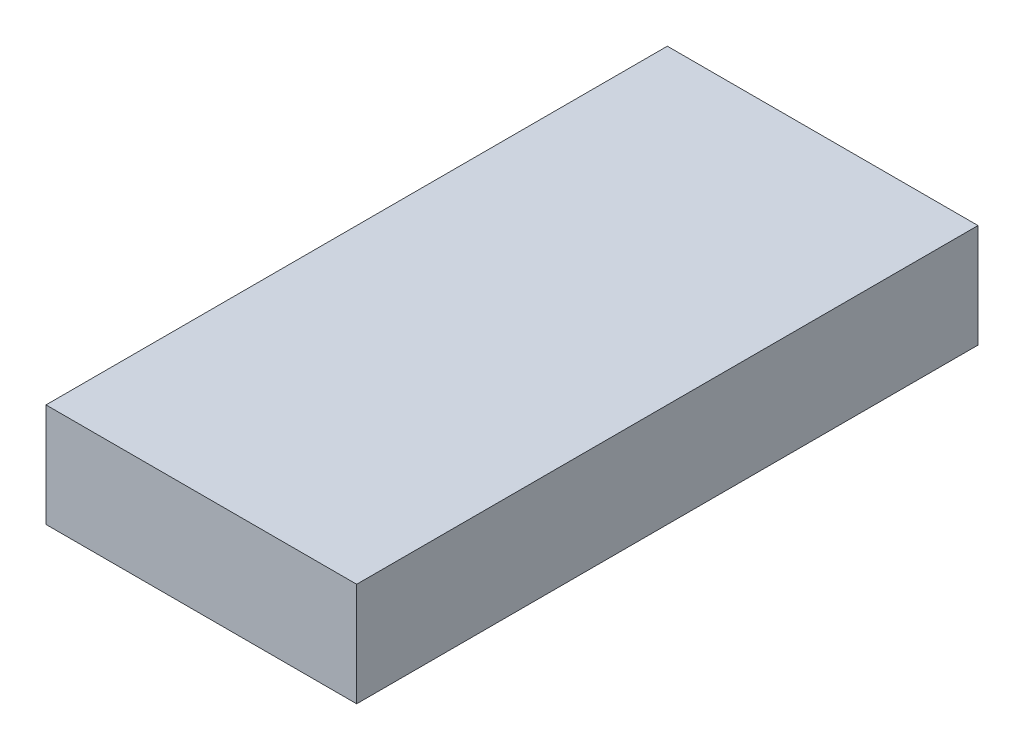
SolidWorks part; units mm, degrees
ref_plane "前视基准面" through (0, 0, 0) normal (0, 0, 1) x (1, 0, 0)
ref_plane "上视基准面" through (0, 0, 0) normal (0, 1, 0) x (1, 0, 0)
ref_plane "右视基准面" through (0, 0, 0) normal (1, 0, 0) x (0, 0, -1)
other "Configuration Table"
sketch "草图1" plane through (0, 0, 0) normal (0, 1, 0) x (1, 0, 0)
  line L1 (-15, -30) -> (15, -30)
  line L2 (-15, -30) -> (-15, 30)
  line L3 (-15, 30) -> (15, 30)
  line L4 (15, -30) -> (15, 30)
  line L5 (-15, -30) -> (15, 30) construction
  line L6 (-15, 30) -> (15, -30) construction
  point P0 (0, 0)
  dimension "D1" = 30
  dimension "D2" = 60
extrude "凸台-拉伸1" add sketch "草图1" along normal blind 10
sketch "草图2" plane through (0, 0, -30) normal (0, 0, -1) x (-1, 0, 0)
  line L0 (-15, 5) -> (-7.5, 5) construction
  line L1 (-15, 10) -> (-15, 0) construction
  line L2 (0, 10) -> (0.0001, 10) construction
  line L3 (-15, 10) -> (15, 10) construction
  line L4 (0.0001, 10) -> (0, 10) construction
  line L5 (0, 10) -> (0.0001, 10) construction
  line L6 (0, 10) -> (0.0001, 10) construction
  line L7 (0, 10) -> (0, 0.0001) construction
  circle A0 centre (-7.5, 5) radius 2
  circle A1 centre (7.5, 5) radius 2
  dimension "D2" = 4
  dimension "D1" = 7.5
extrude "切除-拉伸1" cut sketch "草图2" against normal blind 40
